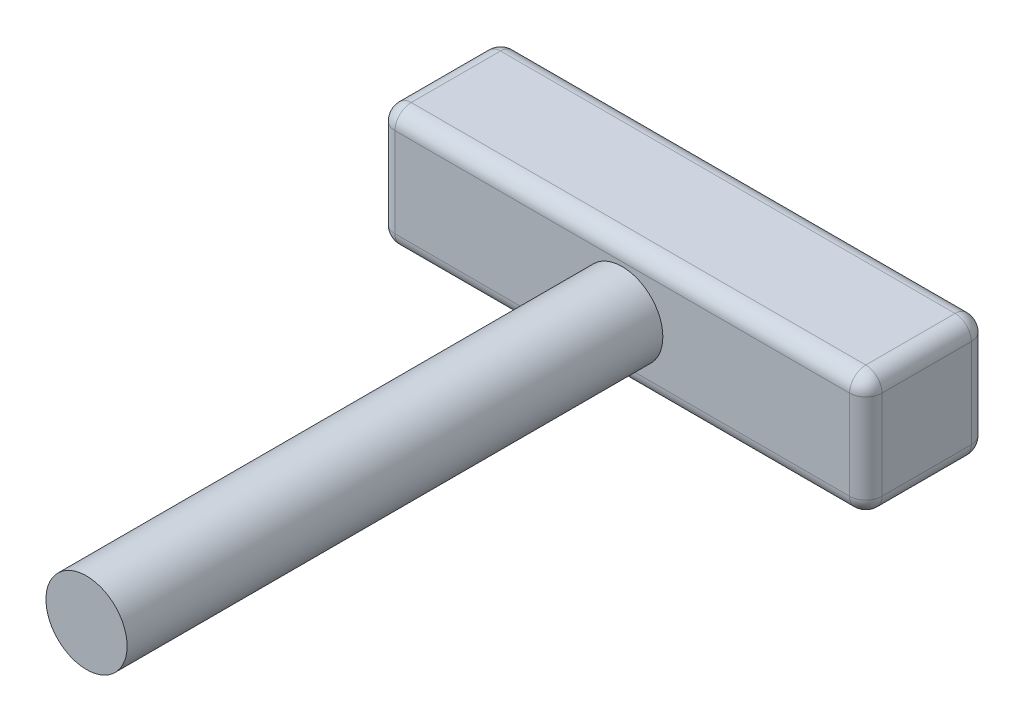
SolidWorks part; units mm, degrees
ref_plane "Front Plane" through (0, 0, 0) normal (0, 0, 1) x (1, 0, 0)
ref_plane "Top Plane" through (0, 0, 0) normal (0, 1, 0) x (1, 0, 0)
ref_plane "Right Plane" through (0, 0, 0) normal (1, 0, 0) x (0, 0, -1)
sketch "Sketch1" plane through (0, 0, 0) normal (1, 0, 0) x (0, 0, -1)
  line L1 (-7.5, -7.5) -> (7.5, -7.5)
  line L2 (-7.5, -7.5) -> (-7.5, 7.5)
  line L3 (-7.5, 7.5) -> (7.5, 7.5)
  line L4 (7.5, -7.5) -> (7.5, 7.5)
  line L5 (-7.5, -7.5) -> (7.5, 7.5) construction
  line L6 (-7.5, 7.5) -> (7.5, -7.5) construction
  point P0 (0, 0)
  dimension "D1" = 15
  dimension "D2" = 15
extrude "Boss-Extrude1" add sketch "Sketch1" along normal blind 60 contours L3 L4 L1 L2
sketch "Sketch3" plane through (0, 0, 7.5) normal (0, 0, 1) x (1, 0, 0)
  line L0 (0, 0) -> (30, 0) construction
  circle A0 centre (30, 0) radius 5
  dimension "D2" = 10
  dimension "D1" = 30
extrude "Boss-Extrude2" add sketch "Sketch3" along normal blind 66
fillet "Fillet1" radius 2 12 edges at (30, 7.5, 7.5) (60, 0, 7.5) (30, -7.5, 7.5) (0, 0, 7.5) (0, 0, -7.5) (0, -7.5, 0) (0, 7.5, 0) (60, 0, -7.5) (60, -7.5, 0) (60, 7.5, 0) (30, -7.5, -7.5) (30, 7.5, -7.5)
